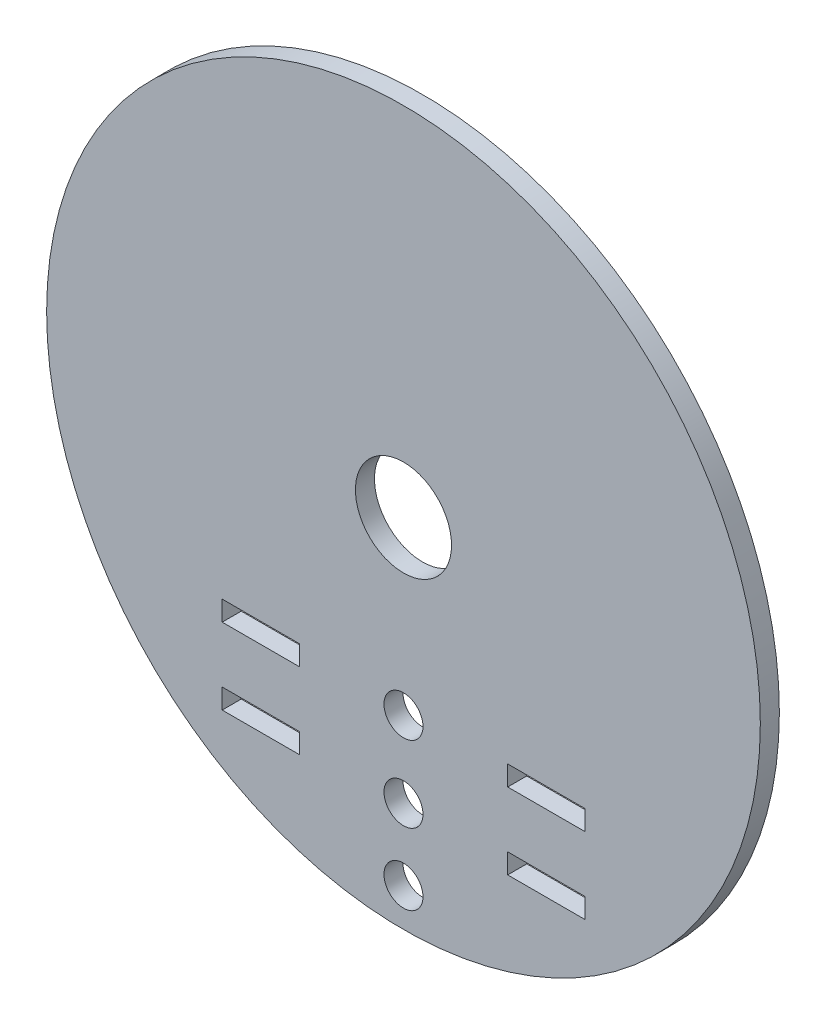
SolidWorks part; units mm, degrees
ref_plane "前视基准面" through (0, 0, 0) normal (0, 0, 1) x (1, 0, 0)
ref_plane "上视基准面" through (0, 0, 0) normal (0, 1, 0) x (1, 0, 0)
ref_plane "右视基准面" through (0, 0, 0) normal (1, 0, 0) x (0, 0, -1)
sketch "草图1" plane through (0, 0, 0) normal (0, 0, 1) x (1, 0, 0)
  line L0 (0, 0) -> (0, 8) construction
  line L1 (0, 8) -> (-15, 8) construction
  line L2 (0, 4) -> (-3.9018, 4) construction
  line L3 (-19.05, 9.05) -> (-10.95, 9.05)
  line L4 (-19.05, 9.05) -> (-19.05, 6.95)
  line L5 (-19.05, 6.95) -> (-10.95, 6.95)
  line L6 (-10.95, 9.05) -> (-10.95, 6.95)
  line L7 (-19.05, 9.05) -> (-10.95, 6.95) construction
  line L8 (-19.05, 6.95) -> (-10.95, 9.05) construction
  line L9 (-10.95, -1.05) -> (-10.95, 1.05)
  line L10 (-19.05, -1.05) -> (-10.95, -1.05)
  line L11 (-19.05, -1.05) -> (-19.05, 1.05)
  line L12 (-19.05, 1.05) -> (-10.95, 1.05)
  line L13 (10.95, 9.05) -> (10.95, 6.95)
  line L14 (19.05, 9.05) -> (10.95, 9.05)
  line L15 (19.05, 9.05) -> (19.05, 6.95)
  line L16 (19.05, 6.95) -> (10.95, 6.95)
  line L17 (19.05, 1.05) -> (10.95, 1.05)
  line L18 (19.05, -1.05) -> (19.05, 1.05)
  line L19 (19.05, -1.05) -> (10.95, -1.05)
  line L20 (10.95, -1.05) -> (10.95, 1.05)
  circle A0 centre (0, 0) radius 2.05
  circle A1 centre (0, 8) radius 2.05
  circle A2 centre (0, 26) radius 5.05
  circle A4 centre (0, 26) radius 12 construction
  circle A6 centre (0, 26) radius 37.5
  circle A7 centre (0, -7.5) radius 2.05
  point P26 (0, 0)
  dimension "D1" = 4.1
  dimension "D3" = 4.1
  dimension "D7" = 10.1
  dimension "D9" = 24
  dimension "D10" = 75
  dimension "D11" = 7.5
  dimension "D2" = 8
  dimension "D4" = 15
  dimension "D5" = 8.1
  dimension "D6" = 2.1
  dimension "D8" = 18
extrude "凸台-拉伸1" add sketch "草图1" along normal blind 2
